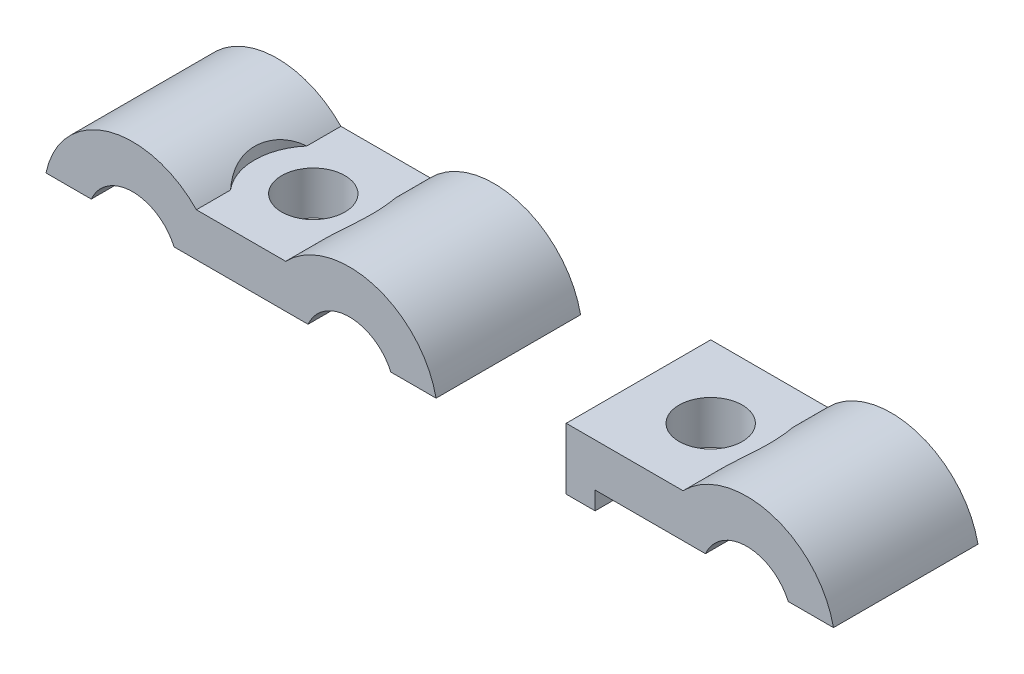
SolidWorks part; units mm, degrees
ref_plane "Front Plane" through (0, 0, 0) normal (0, 0, 1) x (1, 0, 0)
ref_plane "Top Plane" through (0, 0, 0) normal (0, 1, 0) x (1, 0, 0)
ref_plane "Right Plane" through (0, 0, 0) normal (1, 0, 0) x (0, 0, -1)
sketch "Skica1" plane through (0, 0, 0) normal (0, 0, 1) x (1, 0, 0)
  line L0 (0, 0) -> (36, 0) construction
  line L1 (1.2031, 1) -> (55.4878, 1)
  line L2 (1.2031, 3.4) -> (55.4878, 3.4)
  line L3 (30, 3.4) -> (30, 1)
  line L5 (30, 1) -> (31.6, 1)
  line L6 (30, 1) -> (30, 0)
  line L7 (30, 0) -> (31.6, 0)
  line L8 (31.6, 1) -> (31.6, 0)
  circle A0 centre (18, 0) radius 2.5
  circle A1 centre (6, 0) radius 2.5
  circle A2 centre (40, 0) radius 2.5
  circle A3 centre (6, 0) radius 4.9
  circle A4 centre (18, 0) radius 4.9
  circle A5 centre (40, 0) radius 4.9
  dimension "D1" = 5
  dimension "D2" = 5
  dimension "D3" = 5
  dimension "D8" = 12
  dimension "D4" = 2
  dimension "D7" = 6
  dimension "D9" = 40
  dimension "D10" = 10
  dimension "D11" = 1.6
  dimension "D5" = 2.4
  dimension "D6" = 2.4
extrude "Přidat vysunutím1" add sketch "Skica1" along normal blind 8 contours L1 A3 L2 A1 | L2 A3 | A4 L2 A3 L1 | L1 A4 L2 A0 | L2 A4 | L8 L1 L6 L7 | A5 L2 L3 L1 | L1 A5 L2 A2 | L2 A5
sketch "Skica2" plane through (0, 3.4, 0) normal (0, 1, 0) x (1, 0, 0)
  line L0 (9.5285, -4) -> (14.4715, -4) construction
  line L3 (9.5285, -8) -> (9.5285, 0) construction
  line L4 (14.4715, -8) -> (14.4715, 0) construction
  line L5 (36.4715, -4) -> (30, -4) construction
  line L6 (36.4715, -8) -> (36.4715, 0) construction
  line L7 (30, -8) -> (30, 0) construction
  circle A0 centre (12, -4) radius 1.75
  circle A1 centre (34, -4) radius 1.75
  dimension "D1" = 3.5
  dimension "D2" = 3.5
  dimension "D3" = 4
extrude "Odebrat vysunutím1" cut sketch "Skica2" against normal blind 8
sketch "Skica3" plane through (0, 3.4, 0) normal (0, 1, 0) x (1, 0, 0)
  circle A0 centre (12, -4) radius 3.25
  circle A1 centre (34, -4) radius 3.25
  dimension "D1" = 6.5
  dimension "D2" = 6.5
extrude "Odebrat vysunutím2" cut sketch "Skica3" along normal blind 8
